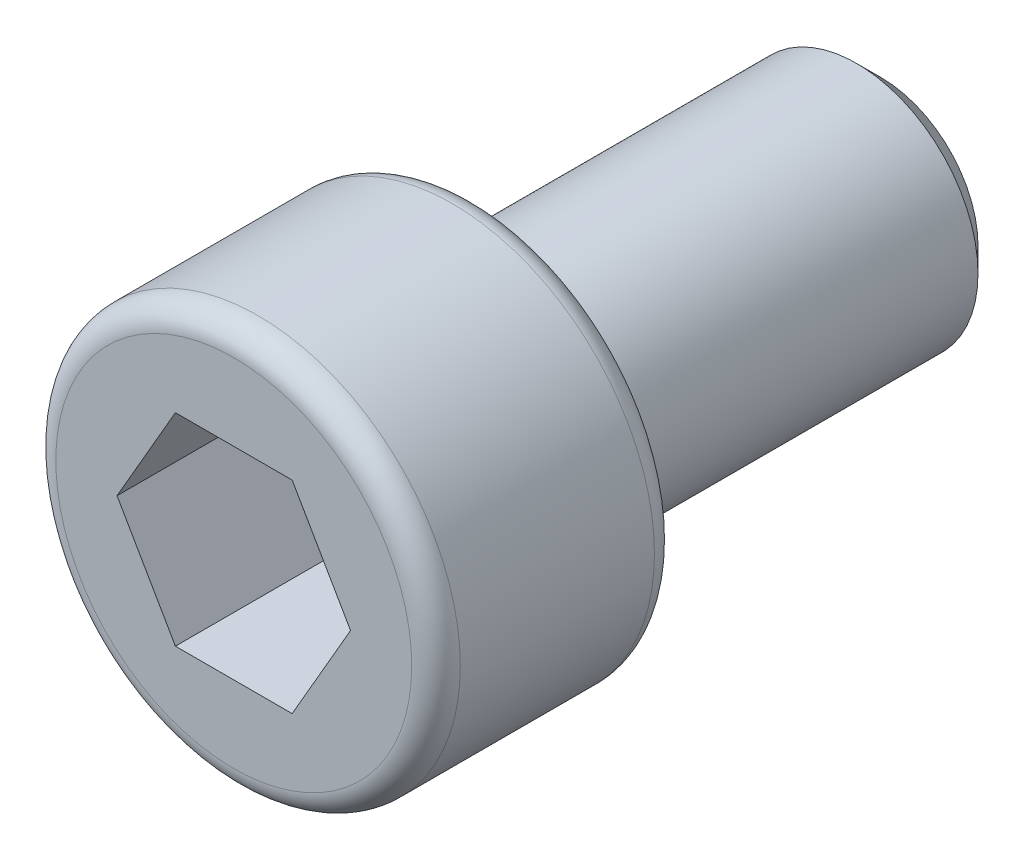
SolidWorks part; units mm, degrees
ref_plane "前视基准面" through (0, 0, 0) normal (0, 0, 1) x (1, 0, 0)
ref_plane "上视基准面" through (0, 0, 0) normal (0, 1, 0) x (1, 0, 0)
ref_plane "右视基准面" through (0, 0, 0) normal (1, 0, 0) x (0, 0, -1)
sketch "草图1" plane through (0, 0, 0) normal (0, 0, 1) x (1, 0, 0)
  circle A0 centre (0, 0) radius 2.5
  dimension "D1" = 5
extrude "凸台-拉伸1" add sketch "草图1" along normal blind 3
sketch "草图2" plane through (0, 0, 0) normal (0, 0, -1) x (-1, 0, 0)
  circle A0 centre (0, 0) radius 1.5
  dimension "D1" = 3
extrude "凸台-拉伸2" add sketch "草图2" along normal blind 5
sketch "草图3" plane through (0, 0, 3) normal (0, 0, 1) x (1, 0, 0)
  line L1 (1.4434, 0) -> (0.7217, 1.25)
  line L2 (0.7217, 1.25) -> (-0.7217, 1.25)
  line L3 (-0.7217, 1.25) -> (-1.4434, 0)
  line L4 (-1.4434, 0) -> (-0.7217, -1.25)
  line L5 (-0.7217, -1.25) -> (0.7217, -1.25)
  line L6 (0.7217, -1.25) -> (1.4434, 0)
  circle A0 centre (0, 0) radius 1.25 construction
  dimension "D1" = 2.5
extrude "切除-拉伸1" cut sketch "草图3" against normal blind 2
chamfer "倒角1" distance 0.3 angle 45 1 edges at (-1.5, 0, -5)
fillet "圆角1" radius 0.3 2 edges at (2.5, 0, 0) (2.5, 0, 3)
